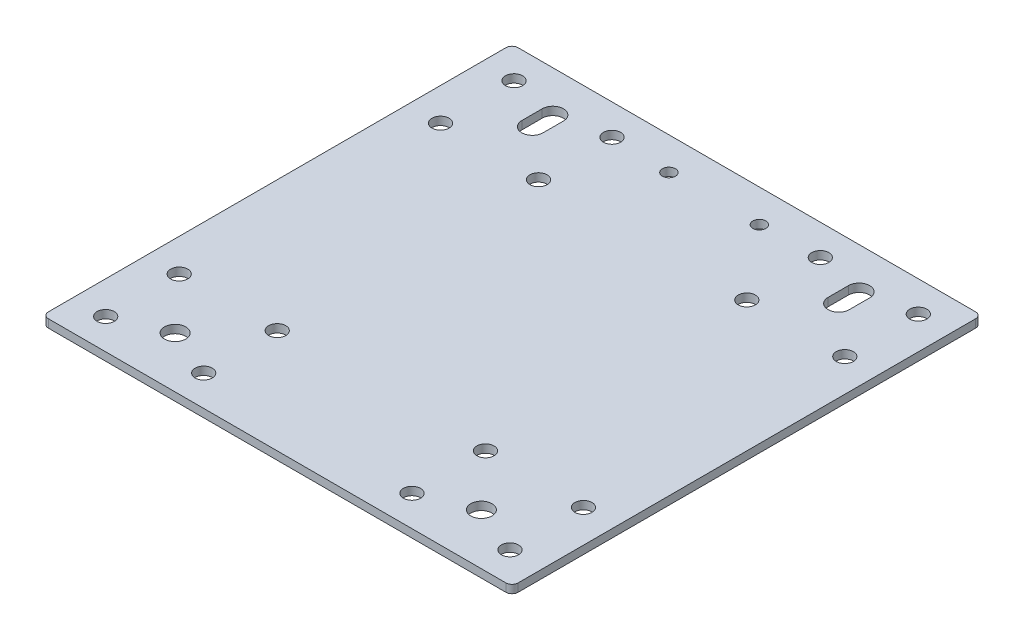
SolidWorks part; units mm, degrees
ref_plane "Front Plane" through (0, 0, 0) normal (0, 0, 1) x (1, 0, 0)
ref_plane "Top Plane" through (0, 0, 0) normal (0, 1, 0) x (1, 0, 0)
ref_plane "Right Plane" through (0, 0, 0) normal (1, 0, 0) x (0, 0, -1)
sketch "Sketch1" plane through (0, 0, 0) normal (0, 1, 0) x (1, 0, 0)
  line L0 (-57.5, 45) -> (57.5, 45) construction
  line L1 (-57.5, -57.5) -> (57.5, -57.5)
  line L2 (-57.5, -57.5) -> (-57.5, 57.5)
  line L3 (-57.5, 57.5) -> (57.5, 57.5)
  line L4 (57.5, -57.5) -> (57.5, 57.5)
  line L5 (-57.5, -57.5) -> (57.5, 57.5) construction
  line L6 (-57.5, 57.5) -> (57.5, -57.5) construction
  line L7 (0, 57.5) -> (0, -57.5) construction
  line L8 (-57.5, 0) -> (57.5, 0) construction
  line L9 (-57.5, -45) -> (57.5, -45) construction
  circle A0 centre (-37.5, 45) radius 2.6
  circle A1 centre (37.5, 45) radius 2.6
  circle A2 centre (37.5, -45) radius 2.6
  circle A3 centre (-37.5, -45) radius 2.6
  point P0 (0, 0)
  dimension "D1" = 5.2
  dimension "D2" = 75
  dimension "D3" = 115
  dimension "D4" = 90
  dimension "D5" = 115
extrude "Boss-Extrude1" add sketch "Sketch1" along normal blind 2
sketch "Sketch2" plane through (0, 2, 0) normal (0, 1, 0) x (1, 0, 0)
  line L0 (-37.5, 57.5) -> (-37.5, -45) construction
  line L1 (57.5, 57.5) -> (-57.5, 57.5) construction
  line L2 (-57.5, -32) -> (57.5, -32) construction
  line L3 (-57.5, 57.5) -> (-57.5, -57.5) construction
  line L4 (57.5, -57.5) -> (57.5, 57.5) construction
  line L5 (-57.5, -41) -> (57.5, -41) construction
  line L6 (0, 57.5) -> (0, -57.5) construction
  line L7 (-57.5, -57.5) -> (57.5, -57.5) construction
  line L8 (-57.5, 0) -> (57.5, 0) construction
  circle A0 centre (-49.5, -32) radius 2.1
  circle A1 centre (-25.5, -32) radius 2.1
  circle A2 centre (-25.5, -50) radius 2.1
  circle A3 centre (-49.5, -50) radius 2.1
  circle A4 centre (25.5, -50) radius 2.1
  circle A5 centre (49.5, -50) radius 2.1
  circle A6 centre (49.5, -32) radius 2.1
  circle A7 centre (25.5, -32) radius 2.1
  circle A8 centre (49.5, 50) radius 2.1
  circle A9 centre (-37.5, -45) radius 2.6 construction
  circle A10 centre (49.5, 32) radius 2.1
  circle A11 centre (25.5, 50) radius 2.1
  circle A12 centre (25.5, 32) radius 2.1
  circle A13 centre (-25.5, 50) radius 2.1
  circle A14 centre (-49.5, 50) radius 2.1
  circle A15 centre (-49.5, 32) radius 2.1
  circle A16 centre (-25.5, 32) radius 2.1
  dimension "D1" = 4.2
  dimension "D2" = 24
  dimension "D4" = 5
  dimension "D3" = 9
  dimension "D5" = 41
extrude "Cut-Extrude1" cut sketch "Sketch2" against normal through all
sketch "Sketch3" plane through (0, 2, 0) normal (0, 1, 0) x (1, 0, 0)
  line L0 (0, -57.5) -> (0, 57.5) construction
  line L1 (-57.5, -57.5) -> (57.5, -57.5) construction
  line L2 (57.5, 57.5) -> (-57.5, 57.5) construction
  line L4 (-8.75, -35) -> (8.75, -35)
  line L5 (-8.75, -35) -> (-8.75, -57.5)
  line L6 (-8.75, -57.5) -> (8.75, -57.5)
  line L7 (8.75, -35) -> (8.75, -57.5)
  line L8 (-8.75, -35) -> (8.75, -57.5) construction
  line L9 (-8.75, -57.5) -> (8.75, -35) construction
  point P6 (0, -46.25)
  dimension "D1" = 17.5
  dimension "D2" = 22.5
extrude "Cut-Extrude2" cut sketch "Sketch3" against normal through all
sketch "Sketch4" plane through (0, 2, 0) normal (0, 1, 0) x (1, 0, 0)
  line L0 (-57.5, 49.5) -> (57.5, 49.5) construction
  line L1 (-57.5, 57.5) -> (-57.5, -57.5) construction
  line L2 (57.5, -57.5) -> (57.5, 57.5) construction
  line L3 (8.75, -35) -> (-8.75, -35) construction
  line L4 (0, 0) -> (0, -35) construction
  line L5 (57.5, 57.5) -> (-57.5, 57.5) construction
  circle A0 centre (-11.075, 49.5) radius 1.6
  circle A1 centre (11.075, 49.5) radius 1.6
  dimension "D2" = 3.2
  dimension "D3" = 22.15
  dimension "D1" = 8
extrude "Cut-Extrude3" cut sketch "Sketch4" against normal through all
sketch "Sketch6" plane through (0, 2, 0) normal (0, 1, 0) x (1, 0, 0)
  line L0 (0, 57.5) -> (0, 0) construction
  line L1 (57.5, 57.5) -> (-57.5, 57.5) construction
  line L2 (-37.5, 45) -> (-37.5, 57.5) construction
  line L3 (-37.5, 47.5) -> (-37.5, 42.5) construction
  line L4 (-34.9, 47.5) -> (-34.9, 42.5)
  line L5 (-40.1, 47.5) -> (-40.1, 42.5)
  line L6 (37.5, 47.5) -> (37.5, 42.5) construction
  line L7 (34.9, 47.5) -> (34.9, 42.5)
  line L8 (40.1, 47.5) -> (40.1, 42.5)
  arc A0 (-34.9, 47.5) -> (-40.1, 47.5) centre (-37.5, 47.5) ccw
  arc A1 (-40.1, 42.5) -> (-34.9, 42.5) centre (-37.5, 42.5) ccw
  arc A2 (34.9, 47.5) -> (40.1, 47.5) centre (37.5, 47.5) cw
  arc A3 (40.1, 42.5) -> (34.9, 42.5) centre (37.5, 42.5) cw
  point P10 (-37.5, 45)
  point P17 (37.5, 45)
  dimension "D2" = 2.6
  dimension "D1" = 5
extrude "Cut-Extrude4" cut sketch "Sketch6" against normal through all
sketch "Sketch7" plane through (0, 2, 0) normal (0, 1, 0) x (1, 0, 0)
  line L1 (-8.75, -35) -> (8.75, -35)
  line L2 (-8.75, -35) -> (-8.75, -57.5)
  line L3 (-8.75, -57.5) -> (8.75, -57.5)
  line L4 (8.75, -35) -> (8.75, -57.5)
extrude "Boss-Extrude2" add sketch "Sketch7" against normal through all
fillet "Fillet1" radius 1.5 4 edges at (-57.5, 1, -57.5) (57.5, 1, -57.5) (57.5, 1, 57.5) (-57.5, 1, 57.5)
